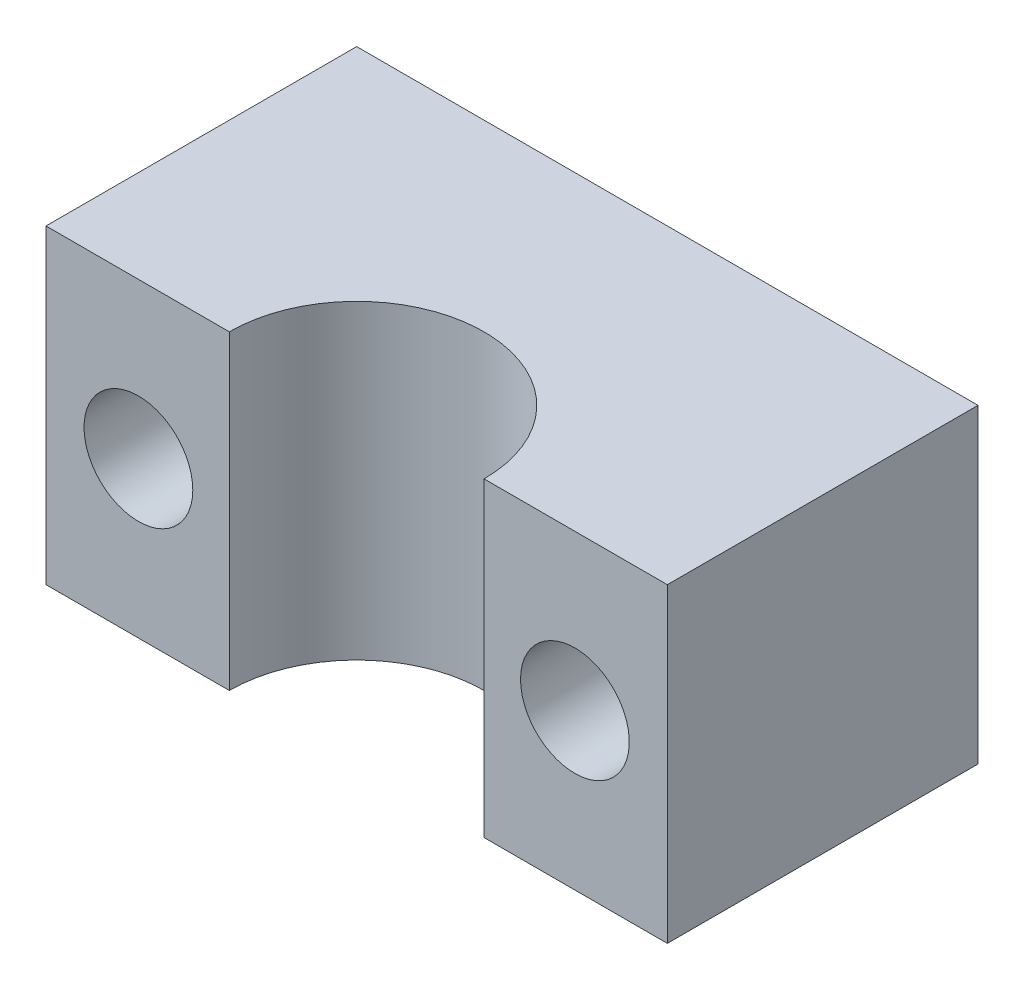
SolidWorks part; units mm, degrees
ref_plane "Alzado" through (0, 0, 0) normal (0, 0, 1) x (1, 0, 0)
ref_plane "Planta" through (0, 0, 0) normal (0, 1, 0) x (1, 0, 0)
ref_plane "Vista lateral" through (0, 0, 0) normal (1, 0, 0) x (0, 0, -1)
sketch "Croquis1" plane through (0, 0, 0) normal (0, 0, 1) x (1, 0, 0)
  line L0 (-6.5583, -2.575) -> (1.6417, -2.575) construction
  line L1 (-12.4583, -2.575) -> (-6.5583, -2.575)
  line L2 (-12.4583, -2.575) -> (-12.4583, 7.425)
  line L3 (-12.4583, 7.425) -> (-6.5583, 7.425)
  line L4 (-6.5583, -2.575) -> (-6.5583, 7.425)
  line L5 (-2.4583, -2.575) -> (-2.4583, 7.425) construction
  line L6 (1.6417, -2.575) -> (1.6417, 7.425)
  line L7 (7.5417, 7.425) -> (1.6417, 7.425)
  line L8 (7.5417, -2.575) -> (7.5417, 7.425)
  line L9 (7.5417, -2.575) -> (1.6417, -2.575)
  circle A0 centre (-9.4833, 2.425) radius 1.75
  circle A1 centre (4.5667, 2.425) radius 1.75
  point P14 (0, 0)
  dimension "D3" = 3.5
  dimension "D4" = 5
  dimension "D5" = 2.925
  dimension "D1" = 5.9
  dimension "D2" = 10
  dimension "D6" = 8.2
extrude "Saliente-Extruir1" add sketch "Croquis1" along normal blind 10
sketch "Croquis3" plane through (0, -2.575, 0) normal (0, -1, 0) x (1, 0, 0)
  line L0 (-6.5583, 10) -> (1.6417, 10) construction
  line L1 (-6.5583, 10) -> (-6.5583, 0)
  line L2 (-6.5583, 10) -> (-6.5583, 0) construction
  line L3 (-6.5583, 0) -> (1.6417, 0)
  line L4 (1.6417, 0) -> (1.6417, 10)
  arc A0 (-6.5583, 10) -> (1.6417, 10) centre (-2.4583, 10) ccw
extrude "Saliente-Extruir2" add sketch "Croquis3" against normal blind 10
